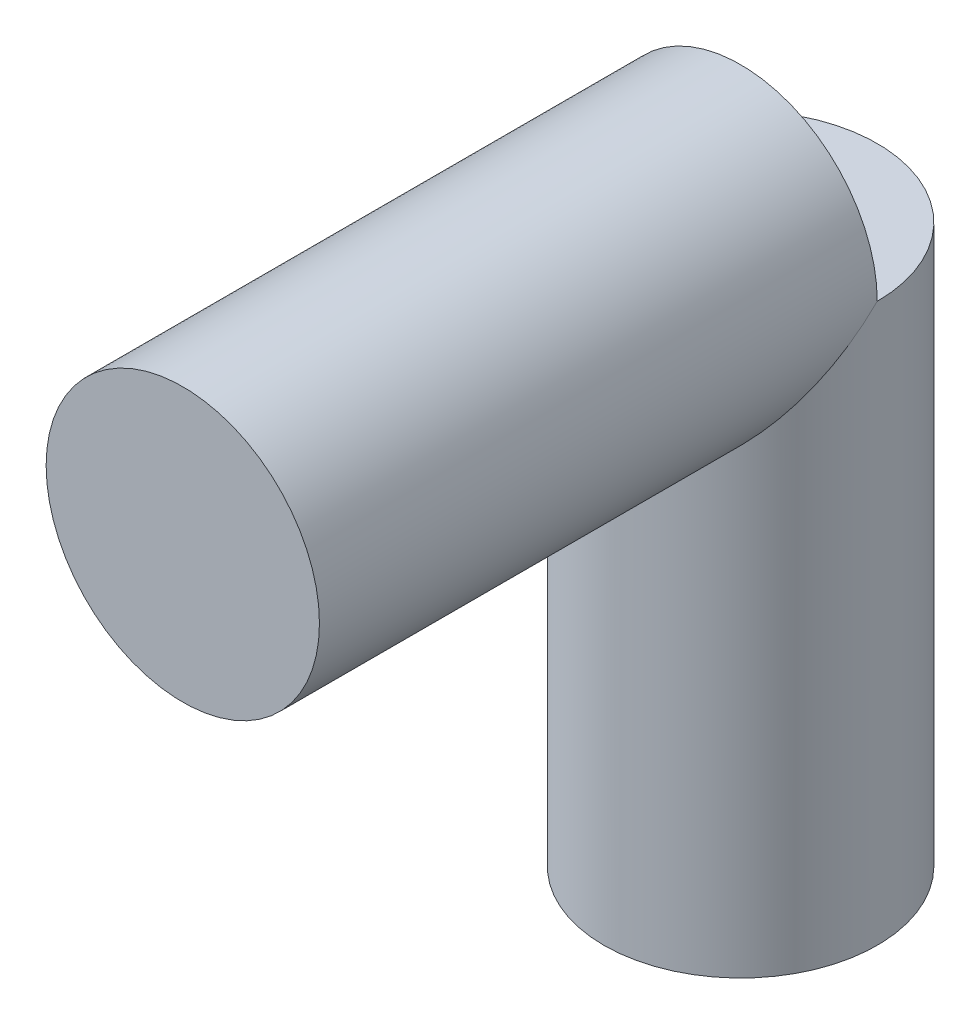
SolidWorks part; units mm, degrees
ref_plane "Front Plane" through (0, 0, 0) normal (0, 0, 1) x (1, 0, 0)
ref_plane "Top Plane" through (0, 0, 0) normal (0, 1, 0) x (1, 0, 0)
ref_plane "Right Plane" through (0, 0, 0) normal (1, 0, 0) x (0, 0, -1)
sketch "Sketch1" plane through (0, 0, 0) normal (0, 1, 0) x (1, 0, 0)
  circle A0 centre (0, 0) radius 4.9
  dimension "D1" = 9.8
extrude "Boss-Extrude1" add sketch "Sketch1" along normal blind 20
sketch "Sketch2" plane through (0, 20, 0) normal (0, 1, 0) x (1, 0, 0)
  circle A0 centre (0, 0) radius 4.9 construction
ref_plane "Plane1" through (0, 0, 0) normal (0, 0, 1) x (1, 0, 0)
sketch "Sketch3" plane through (0, 0, 0) normal (0, 0, 1) x (1, 0, 0)
  line L0 (4.9, 20) -> (-4.9, 20) construction
  circle A0 centre (0, 20) radius 4.9
extrude "Boss-Extrude2" add sketch "Sketch3" along normal blind 20
